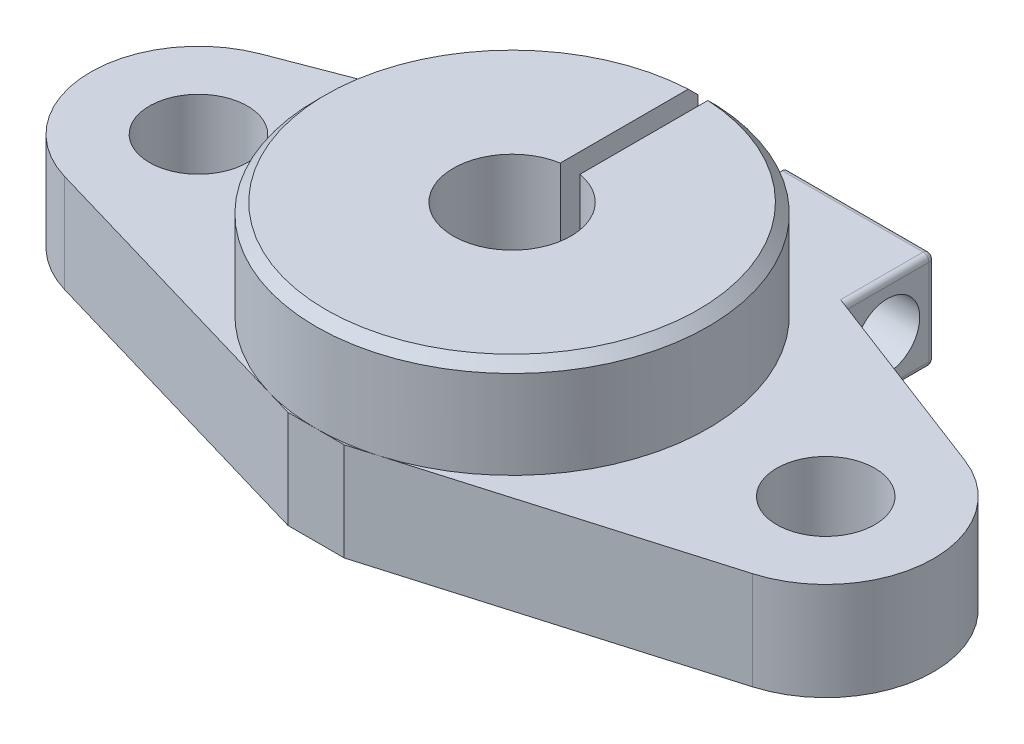
SolidWorks part; units mm, degrees
ref_plane "Front" through (0, 0, 0) normal (0, 0, 1) x (1, 0, 0)
ref_plane "Top" through (0, 0, 0) normal (0, 1, 0) x (1, 0, 0)
ref_plane "Right" through (0, 0, 0) normal (1, 0, 0) x (0, 0, -1)
sketch "草图1" plane through (0, 0, 0) normal (0, 1, 0) x (1, 0, 0)
  line L0 (-52.0732, 0) -> (63.1086, 0) construction
  line L1 (0, 37.0375) -> (0, -33.9476) construction
  line L2 (-17.9662, 5.1365) -> (-7.9859, 8.9569)
  line L3 (-7.9859, 8.9569) -> (-7.9859, 13.5794)
  line L4 (-7.9859, 13.5794) -> (7.9859, 13.5794)
  line L5 (-17.5469, -5.278) -> (-1.4352, -10)
  line L6 (1.4352, -10) -> (-1.4352, -10)
  line L7 (-1.4352, -10) -> (0, -10.4206) construction
  line L8 (7.9859, 8.9569) -> (7.9859, 13.5794)
  line L9 (17.9662, 5.1365) -> (7.9859, 8.9569)
  line L10 (17.5469, -5.278) -> (1.4352, -10)
  circle A0 centre (-16, 0) radius 2.5
  circle A1 centre (0, 0) radius 3
  arc A2 (-17.9662, 5.1365) -> (-17.5469, -5.278) centre (-16, 0) ccw
  circle A3 centre (0, 0) radius 10 construction
  circle A4 centre (16, 0) radius 2.5
  arc A5 (17.9662, 5.1365) -> (17.5469, -5.278) centre (16, 0) cw
  circle A6 centre (0, 0) radius 12 construction
  point P16 (0, 13.5794)
  point P23 (0, -10)
  dimension "D1" = 5
  dimension "D3" = 6
  dimension "D4" = 5.5
  dimension "D7" = 20
  dimension "D6" = 24
  dimension "D2" = 16
  dimension "D5" = 24
extrude "凸台-拉伸1" add sketch "草图1" along normal blind 5
sketch "草图2" plane through (0, 5, 0) normal (0, 1, 0) x (1, 0, 0)
  circle A0 centre (0, 0) radius 3
  circle A1 centre (0, 0) radius 10
  dimension "D1" = 6
extrude "凸台-拉伸2" add sketch "草图2" along normal blind 5
fillet "圆角1" radius 0.3 8 edges at (7.9859, 0, -11.2681) (7.9859, 5, -11.2681) (-7.9859, 0, -11.2681) (-7.9859, 5, -11.2681) (7.9859, 2.5, -13.5794) (-7.9859, 2.5, -13.5794) (0, 0, -13.5794) (0, 5, -13.5794)
chamfer "倒角1" distance 0.5 angle 45 1 edges at (0, 10, 10)
sketch "草图3" plane through (0, 10, 0) normal (0, 1, 0) x (1, 0, 0)
  line L0 (0, 18.2415) -> (0, 0) construction
  line L1 (-24.0719, 0) -> (27.9868, 0) construction
  line L2 (7.9859, 13.5794) -> (-7.9859, 13.5794) construction
  line L3 (-0.5, 0) -> (0.5, 0)
  line L4 (-0.5, 0) -> (-0.5, 13.5794)
  line L5 (-0.5, 13.5794) -> (0.5, 13.5794)
  line L6 (0.5, 0) -> (0.5, 13.5794)
  dimension "D1" = 1
  dimension "D2" = 0.5
extrude "切除-拉伸1" cut sketch "草图3" against normal up to next
sketch "草图4" plane through (-7.9859, 0, 0) normal (-1, 0, 0) x (0, 0, 1)
  line L0 (-8.9569, 2.5) -> (-11.1569, 2.5) construction
  line L1 (-8.9569, 4.7) -> (-8.9569, 0.3) construction
  circle A0 centre (-11.1569, 2.5) radius 1.7
  point P6 (-11.2584, 2.5)
  point P7 (-11.5117, 2.5)
  dimension "D1" = 3.4
  dimension "D2" = 2.2
hole_wizard "M4 螺纹孔1" positions "3D草图1" profile "草图5" tap size "M4" standard "GB" end condition through all
sketch3d "3D草图1"
  point P0 (-7.9859, 2.5, -11.1569)
sketch "草图5" plane through (-7.9859, 2.5, -11.1569) normal (0, 1, 0) x (0, 0, 1)
  line L0 (0, 0) -> (0, 29.4859)
  line L1 (0, 29.4859) -> (1.65, 29.4859)
  line L2 (1.65, 29.4859) -> (1.65, 0)
  line L5 (1.65, 0) -> (0, 0)
  line L11 (0, -6.35) -> (0, 107.95) construction
  dimension "通孔螺纹孔钻头直径" = 3.3
  dimension "通孔螺纹孔钻头深度" = 29.4859
cosmetic thread "孔螺蚊线1" parameters "D2"=4
